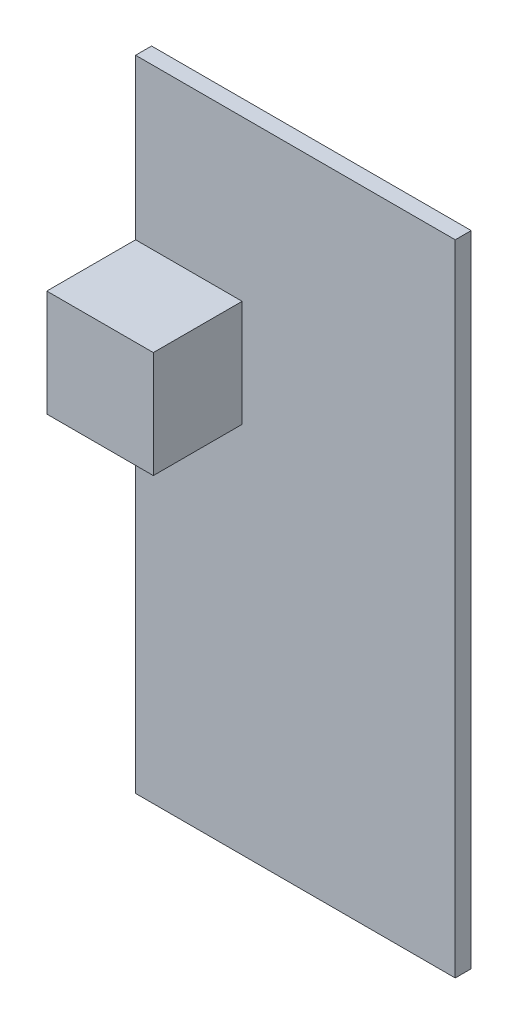
SolidWorks part; units mm, degrees
ref_plane "Alzado" through (0, 0, 0) normal (0, 0, 1) x (1, 0, 0)
ref_plane "Planta" through (0, 0, 0) normal (0, 1, 0) x (1, 0, 0)
ref_plane "Vista lateral" through (0, 0, 0) normal (1, 0, 0) x (0, 0, -1)
sketch "Croquis1" plane through (0, 0, 0) normal (0, 0, 1) x (1, 0, 0)
  line L1 (-5.8468, 3.7709) -> (12.1532, 3.7709)
  line L2 (-5.8468, 3.7709) -> (-5.8468, -32.2291)
  line L3 (-5.8468, -32.2291) -> (12.1532, -32.2291)
  line L4 (12.1532, 3.7709) -> (12.1532, -32.2291)
  dimension "D1" = 18
  dimension "D2" = 36
extrude "Saliente-Extruir1" add sketch "Croquis1" along normal blind 0.9
sketch "Croquis2" plane through (0, 0, 0.9) normal (0, 0, 1) x (1, 0, 0)
  line L0 (-5.8468, 3.7709) -> (-5.8468, -32.2291) construction
  line L1 (-5.8468, -11.2291) -> (0.1532, -11.2291)
  line L2 (-5.8468, -11.2291) -> (-5.8468, -5.2291)
  line L3 (-5.8468, -5.2291) -> (0.1532, -5.2291)
  line L4 (0.1532, -11.2291) -> (0.1532, -5.2291)
  line L5 (12.1532, 3.7709) -> (-5.8468, 3.7709) construction
  dimension "D1" = 6
  dimension "D2" = 6
  dimension "D3" = 9
extrude "Saliente-Extruir2" add sketch "Croquis2" along normal blind 5
